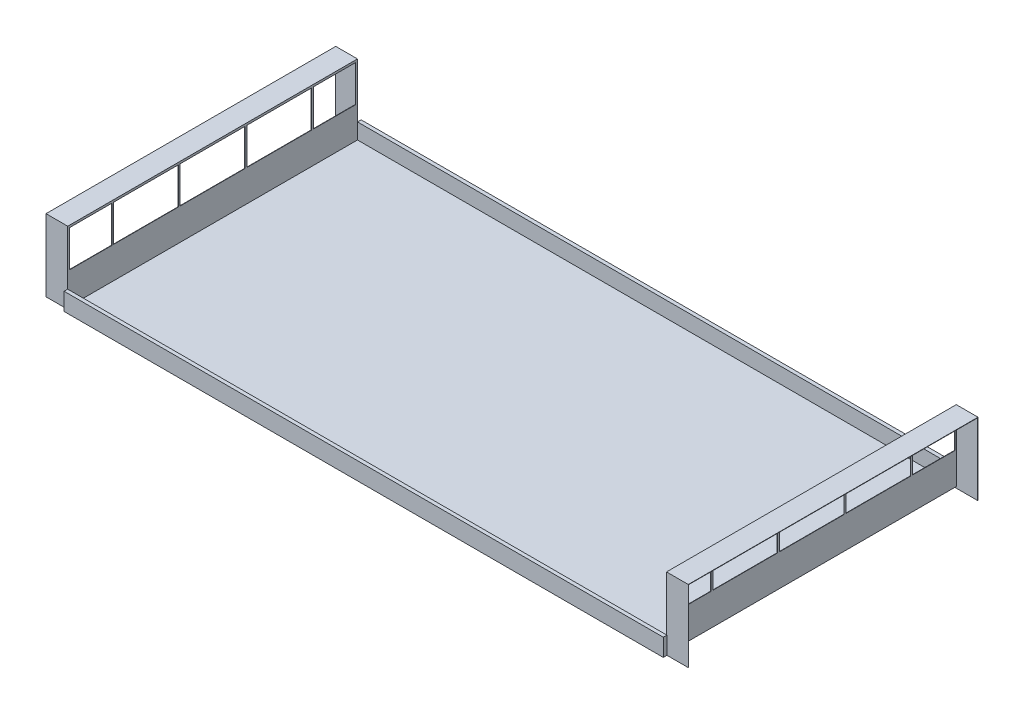
SolidWorks part; units mm, degrees
ref_plane "Front Plane" through (0, 0, 0) normal (0, 0, 1) x (1, 0, 0)
ref_plane "Top Plane" through (0, 0, 0) normal (0, 1, 0) x (1, 0, 0)
ref_plane "Right Plane" through (0, 0, 0) normal (1, 0, 0) x (0, 0, -1)
sketch "Sketch1" plane through (0, 0, 0) normal (0, 1, 0) x (1, 0, 0)
  line L1 (0, 0) -> (16535.4, 0)
  line L2 (0, 0) -> (0, 8001)
  line L3 (0, 8001) -> (16535.4, 8001)
  line L4 (16535.4, 0) -> (16535.4, 8001)
  dimension "D1" = 16535.4
  dimension "D2" = 8001
extrude "Boss-Extrude1" add sketch "Sketch1" along normal blind 50
sketch "Sketch2" plane through (0, 0, 0) normal (0, 1, 0) x (1, 0, 0)
  line L0 (0, 8001) -> (0, 0) construction
  line L1 (0, 0) -> (-600, 0)
  line L2 (0, 0) -> (0, 8001)
  line L3 (0, 8001) -> (-600, 8001)
  line L4 (-600, 0) -> (-600, 8001)
  line L5 (16535.4, 0) -> (16535.4, 8001) construction
  line L6 (16535.4, 0) -> (17135.4, 0)
  line L7 (16535.4, 0) -> (16535.4, 8001)
  line L8 (16535.4, 8001) -> (17135.4, 8001)
  line L9 (17135.4, 0) -> (17135.4, 8001)
  line L10 (16535.4, 8001) -> (0, 8001) construction
  line L11 (0, 0) -> (16535.4, 0) construction
  dimension "D1" = 600
  dimension "D2" = 600
  dimension "D3" = 0
  dimension "D4" = 0
  dimension "D5" = 0
  dimension "D6" = 0
extrude "Boss-Extrude2" add sketch "Sketch2" along normal blind 1988.82
sketch "Sketch3" plane through (0, 0, 0) normal (0, 1, 0) x (1, 0, 0)
  line L0 (17135.4, 8001) -> (-600, 8001) construction
  line L1 (0, 8001) -> (16546.2431, 8001)
  line L2 (0, 8001) -> (0, 8101)
  line L3 (0, 8101) -> (16546.2431, 8101)
  line L4 (16546.2431, 8001) -> (16546.2431, 8101)
  line L6 (0, 0) -> (16546.2431, 0)
  line L7 (0, 0) -> (0, -100)
  line L8 (0, -100) -> (16546.2431, -100)
  line L9 (16546.2431, 0) -> (16546.2431, -100)
  point P11 (0, 0)
  dimension "D1" = 100
  dimension "D2" = 100
extrude "Boss-Extrude12" add sketch "Sketch3" against normal blind 1 and the other way blind 482.6 separate body
shell "Shell1" thickness 10
sketch "Sketch5" plane through (-10, 0, 0) normal (-1, 0, 0) x (0, 0, 1)
  line L0 (-7991, 1978.82) -> (-10, 1978.82) construction
  line L1 (-6732.74, 920) -> (-4944.58, 920)
  line L2 (-6732.74, 920) -> (-6732.74, 1928.82)
  line L3 (-6732.74, 1928.82) -> (-4944.58, 1928.82)
  line L4 (-4944.58, 920) -> (-4944.58, 1928.82)
  line L5 (-4894.58, 1928.82) -> (-3106.42, 1928.82)
  line L6 (-4894.58, 1928.82) -> (-4894.58, 920)
  line L7 (-4894.58, 920) -> (-3106.42, 920)
  line L8 (-3106.42, 1928.82) -> (-3106.42, 920)
  line L9 (-3056.42, 1928.82) -> (-1268.26, 1928.82)
  line L10 (-3056.42, 1928.82) -> (-3056.42, 920)
  line L11 (-3056.42, 920) -> (-1268.26, 920)
  line L12 (-1268.26, 1928.82) -> (-1268.26, 920)
  line L13 (-6782.74, 1928.82) -> (-7951, 1928.82)
  line L14 (-6782.74, 1928.82) -> (-6782.74, 920)
  line L15 (-6782.74, 920) -> (-7951, 920)
  line L16 (-7951, 1928.82) -> (-7951, 920)
  line L17 (-1218.26, 1928.82) -> (-50, 1928.82)
  line L18 (-1218.26, 1928.82) -> (-1218.26, 920)
  line L19 (-1218.26, 920) -> (-50, 920)
  line L20 (-50, 1928.82) -> (-50, 920)
  line L21 (-10, 1978.82) -> (-7991, 1978.82) construction
  line L22 (-8001, 1988.82) -> (-8001, 0) construction
  line L23 (0, 1988.82) -> (0, 0) construction
  line L24 (-7991, 40) -> (-10, 40) construction
  line L25 (-3106.42, 920) -> (-3098.0941, 924.8174)
  dimension "D1" = 50
  dimension "D3" = 50
  dimension "D4" = 50
  dimension "D5" = 50
  dimension "D6" = 50
  dimension "D7" = 50
  dimension "D8" = 50
  dimension "D9" = 50
  dimension "D11" = 50
  dimension "D12" = 880
  dimension "D13" = 880
  dimension "D14" = 880
  dimension "D15" = 880
  dimension "D16" = 880
  dimension "D17" = 1788.16
  dimension "D18" = 1788.16
  dimension "D19" = 1168.26
  dimension "D20" = 1168.26
extrude "Cut-Extrude1" cut sketch "Sketch5" against normal through all contours L13 L16 L15 L14 | L12 L9 L10 L11 | L20 L17 L18 L19 | L1 L4 L3 L2 | L8 L5 L6 L7
